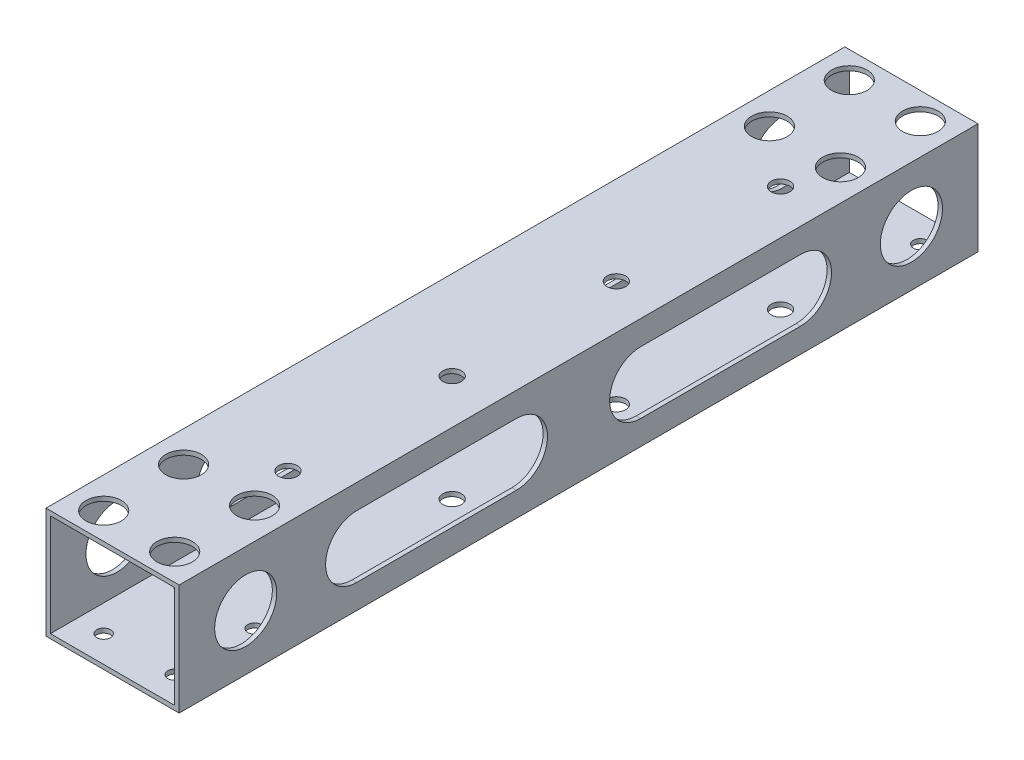
SolidWorks part; units mm, degrees
material "6061 合金"
ref_plane "前视基准面" through (0, 0, 0) normal (0, 0, 1) x (1, 0, 0)
ref_plane "上视基准面" through (0, 0, 0) normal (0, 1, 0) x (1, 0, 0)
ref_plane "右视基准面" through (0, 0, 0) normal (1, 0, 0) x (0, 0, -1)
other "Configuration Table"
sketch "草图1" plane through (0, 0, 0) normal (0, 0, 1) x (1, 0, 0)
  line L1 (-15, 12.5) -> (15, 12.5)
  line L2 (-15, 12.5) -> (-15, -12.5)
  line L3 (-15, -12.5) -> (15, -12.5)
  line L4 (15, 12.5) -> (15, -12.5)
  line L5 (-15, 12.5) -> (15, -12.5) construction
  line L6 (-15, -12.5) -> (15, 12.5) construction
  line L7 (-14, 11.5) -> (14, 11.5)
  line L8 (-14, 11.5) -> (-14, -11.5)
  line L9 (-14, -11.5) -> (14, -11.5)
  line L10 (14, 11.5) -> (14, -11.5)
  line L11 (-14, 11.5) -> (14, -11.5) construction
  line L12 (-14, -11.5) -> (14, 11.5) construction
  point P0 (0, 0)
  point P6 (0, 0)
  dimension "D1" = 30
  dimension "D2" = 25
  dimension "D3" = 1
  dimension "D4" = 1
extrude "凸台-拉伸1" add sketch "草图1" along normal mid plane 180
sketch "草图2" plane through (0, 12.5, 0) normal (0, 1, 0) x (1, 0, 0)
  circle A0 centre (5, 55.51) radius 2.1
  circle A1 centre (5, -55.49) radius 2.1
  circle A2 centre (5, -18.49) radius 2.1
  circle A3 centre (5, 18.51) radius 2.1
  dimension "D1" = 4.2
extrude "切除-拉伸1" cut sketch "草图2" against normal blind 30
sketch "草图3" plane through (0, 12.5, 0) normal (0, 1, 0) x (1, 0, 0)
  circle A0 centre (8, 84) radius 1.55
  circle A1 centre (8, 66) radius 1.55
  circle A2 centre (-8, 84) radius 1.55
  circle A3 centre (-8, 66) radius 1.55
  circle A4 centre (8, -66) radius 1.55
  circle A5 centre (-8, -66) radius 1.55
  circle A6 centre (-8, -84) radius 1.55
  circle A7 centre (8, -84) radius 1.55
  dimension "D1" = 3.1
extrude "切除-拉伸2" cut sketch "草图3" against normal blind 30
sketch "草图4" plane through (0, 12.5, 0) normal (0, 1, 0) x (1, 0, 0)
  circle A0 centre (8, -84) radius 4
  circle A1 centre (-8, -84) radius 4
  circle A2 centre (-8, -66) radius 4
  circle A3 centre (8, -66) radius 4
  circle A4 centre (-8, 66) radius 4
  circle A5 centre (8, 66) radius 4
  circle A6 centre (8, 84) radius 4
  circle A7 centre (-8, 84) radius 4
  dimension "D1" = 8
extrude "切除-拉伸3" cut sketch "草图4" against normal blind 10
sketch "草图5" plane through (-15, 0, 0) normal (-1, 0, 0) x (0, 0, 1)
  line L0 (90, 12.5) -> (90, -12.5) construction
  line L5 (14, 0) -> (50, 0) construction
  line L6 (14, 7) -> (50, 7)
  line L7 (14, -7) -> (50, -7)
  line L8 (0, -24.9209) -> (0, 23.1266) construction
  line L9 (-14, 0) -> (-50, 0) construction
  line L10 (-14, 7) -> (-50, 7)
  line L11 (-14, -7) -> (-50, -7)
  arc A4 (14, 7) -> (14, -7) centre (14, 0) ccw
  arc A5 (50, -7) -> (50, 7) centre (50, 0) ccw
  circle A6 centre (75, 0) radius 7
  arc A7 (-14, 7) -> (-14, -7) centre (-14, 0) cw
  arc A8 (-50, -7) -> (-50, 7) centre (-50, 0) cw
  circle A9 centre (-75, 0) radius 7
  point P1 (0, -0.8972)
  point P8 (32, 0)
  point P19 (-32, 0)
  dimension "D2" = 7
  dimension "D1" = 7
  dimension "D3" = 50
  dimension "D4" = 15
extrude "切除-拉伸4" cut sketch "草图5" against normal blind 30
